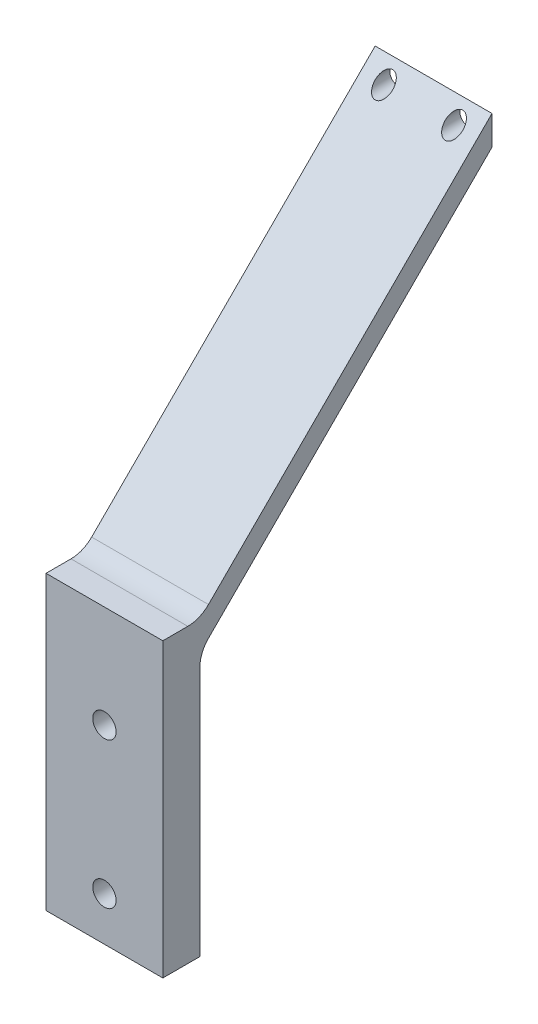
SolidWorks part; units mm, degrees
ref_plane "Front Plane" through (0, 0, 0) normal (0, 0, 1) x (1, 0, 0)
ref_plane "Top Plane" through (0, 0, 0) normal (0, 1, 0) x (1, 0, 0)
ref_plane "Right Plane" through (0, 0, 0) normal (1, 0, 0) x (0, 0, -1)
sketch "Sketch1" plane through (0, 0, 0) normal (0, 0, 1) x (1, 0, 0)
  line L1 (0, 0) -> (20, 0)
  line L2 (0, 0) -> (0, 40)
  line L3 (0, 40) -> (20, 40)
  line L4 (20, 0) -> (20, 40)
  circle A0 centre (10, 32.5) radius 2
  circle A1 centre (10, 7.5) radius 2
  dimension "D5" = 4
  dimension "D1" = 20
  dimension "D2" = 40
  dimension "D3" = 10
  dimension "D4" = 7.5
  dimension "D6" = 25
extrude "Boss-Extrude1" add sketch "Sketch1" along normal blind 6.35
sketch "Sketch2" plane through (0, 40, 0) normal (0, 1, 0) x (1, 0, 0)
  line L1 (0, 0) -> (20, 0)
  line L2 (0, 0) -> (0, -6.35)
  line L3 (0, -6.35) -> (20, -6.35)
  line L4 (20, 0) -> (20, -6.35)
extrude "Boss-Extrude2" add sketch "Sketch2" along normal blind 10
sketch "Sketch3" plane through (20, 0, 0) normal (1, 0, 0) x (0, 0, -1)
  line L0 (50, 100) -> (50, 95)
  line L1 (0, 0) -> (0, 50) construction
  line L2 (0, 45) -> (0, 50)
  line L3 (0, 50) -> (50, 100)
  line L4 (50, 95) -> (0, 45)
  dimension "D1" = 50
  dimension "D2" = 50
  dimension "D3" = 5
  dimension "D4" = 5
extrude "Boss-Extrude3" add sketch "Sketch3" against normal up to surface (20 mm away) up to face at (0, 25, 3.175)
sketch "Sketch4" plane through (0, 0, -50) normal (0, 0, -1) x (-1, 0, 0)
  line L0 (-20, 95) -> (-20, 100) construction
  circle A0 centre (-16, 97.5) radius 1.5
  circle A1 centre (-4, 97.5) radius 1.5
  point P4 (0, 0)
  point P5 (0, 0)
  point P8 (-20, 97.5)
  dimension "D1" = 3
  dimension "D2" = 3
  dimension "D3" = 12
  dimension "D4" = 4
extrude "Cut-Extrude1" cut sketch "Sketch4" against normal blind 23.2
fillet "Fillet1" radius 5 2 edges at (10, 45, 0) (10, 50, 0)
